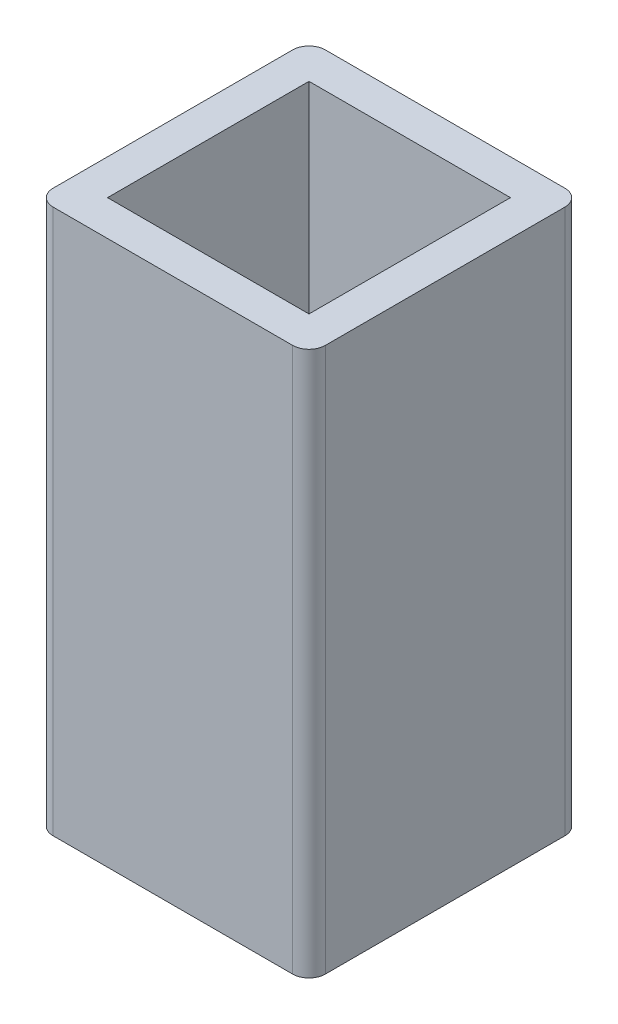
SolidWorks part; units mm, degrees
ref_plane "Front Plane" through (0, 0, 0) normal (0, 0, 1) x (1, 0, 0)
ref_plane "Top Plane" through (0, 0, 0) normal (0, 1, 0) x (1, 0, 0)
ref_plane "Right Plane" through (0, 0, 0) normal (1, 0, 0) x (0, 0, -1)
sketch "Sketch1" plane through (0, 0, 0) normal (0, 1, 0) x (1, 0, 0)
  line L1 (-5.588, -6.35) -> (5.588, -6.35)
  line L2 (-6.35, -5.588) -> (-6.35, 5.588)
  line L3 (-5.588, 6.35) -> (5.588, 6.35)
  line L4 (6.35, -5.588) -> (6.35, 5.588)
  line L5 (0, 6.35) -> (0, -6.35) construction
  line L6 (-6.35, 0) -> (6.35, 0) construction
  line L10 (-4.699, -4.699) -> (-4.699, 4.699)
  line L11 (-4.699, 4.699) -> (4.699, 4.699)
  line L12 (4.699, -4.699) -> (4.699, 4.699)
  line L13 (-4.699, -4.699) -> (4.699, -4.699)
  arc A0 (-5.588, -6.35) -> (-6.35, -5.588) centre (-5.588, -5.588) cw
  arc A1 (5.588, -6.35) -> (6.35, -5.588) centre (5.588, -5.588) ccw
  arc A2 (5.588, 6.35) -> (6.35, 5.588) centre (5.588, 5.588) cw
  arc A3 (-6.35, 5.588) -> (-5.588, 6.35) centre (-5.588, 5.588) cw
  arc A8 (-4.699, 4.699) -> (-4.699, 4.699) centre (-4.699, 4.699) cw
  arc A9 (4.699, 4.699) -> (4.699, 4.699) centre (4.699, 4.699) cw
  arc A10 (4.699, -4.699) -> (4.699, -4.699) centre (4.699, -4.699) ccw
  arc A11 (-4.699, -4.699) -> (-4.699, -4.699) centre (-4.699, -4.699) cw
  point P0 (0, 0)
  point P11 (6.35, 6.35)
  point P14 (-6.35, 6.35)
  dimension "D2" = 0.762
  dimension "D1" = 12.7
  dimension "D3" = 1.651
extrude "Boss-Extrude1" add sketch "Sketch1" along normal blind 25.4
